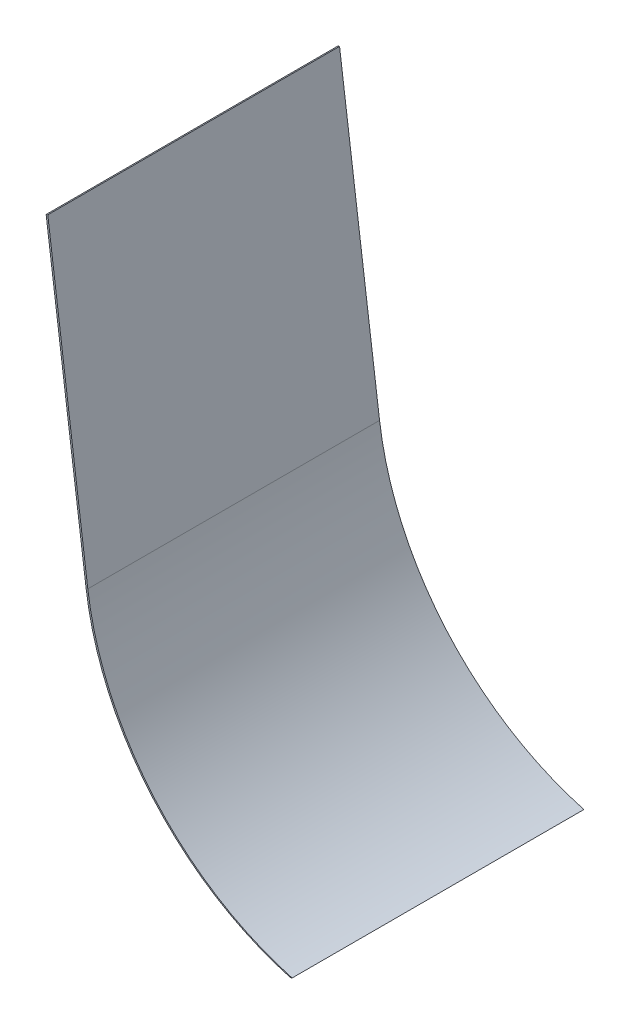
SolidWorks part; units mm, degrees
material "3003-H14"
ref_plane "Front Plane" through (0, 0, 0) normal (0, 0, 1) x (1, 0, 0)
ref_plane "Top Plane" through (0, 0, 0) normal (0, 1, 0) x (1, 0, 0)
ref_plane "Right Plane" through (0, 0, 0) normal (1, 0, 0) x (0, 0, -1)
sketch "Sketch1" plane through (0, 0, 0) normal (0, 0, 1) x (1, 0, 0)
  line L1 (-22.2558, 1100.1347) -> (51.3116, 541.3347)
  line L3 (-19.2252, 1101.0813) -> (54.3422, 542.2813)
  line L4 (426.9432, 109.5347) -> (429.9738, 110.4813)
  line L5 (-22.2558, 1100.1347) -> (-19.2252, 1101.0813)
  arc A0 (51.3116, 541.3347) -> (426.9432, 109.5347) centre (565.0612, 608.9711) ccw
  arc A1 (54.3422, 542.2813) -> (429.9738, 110.4813) centre (568.0918, 609.9177) ccw
  point P4 (426.9432, 109.5347)
  dimension "D3" = 3.175
extrude "Boss-Extrude1" add sketch "Sketch1" along normal blind 536.448
